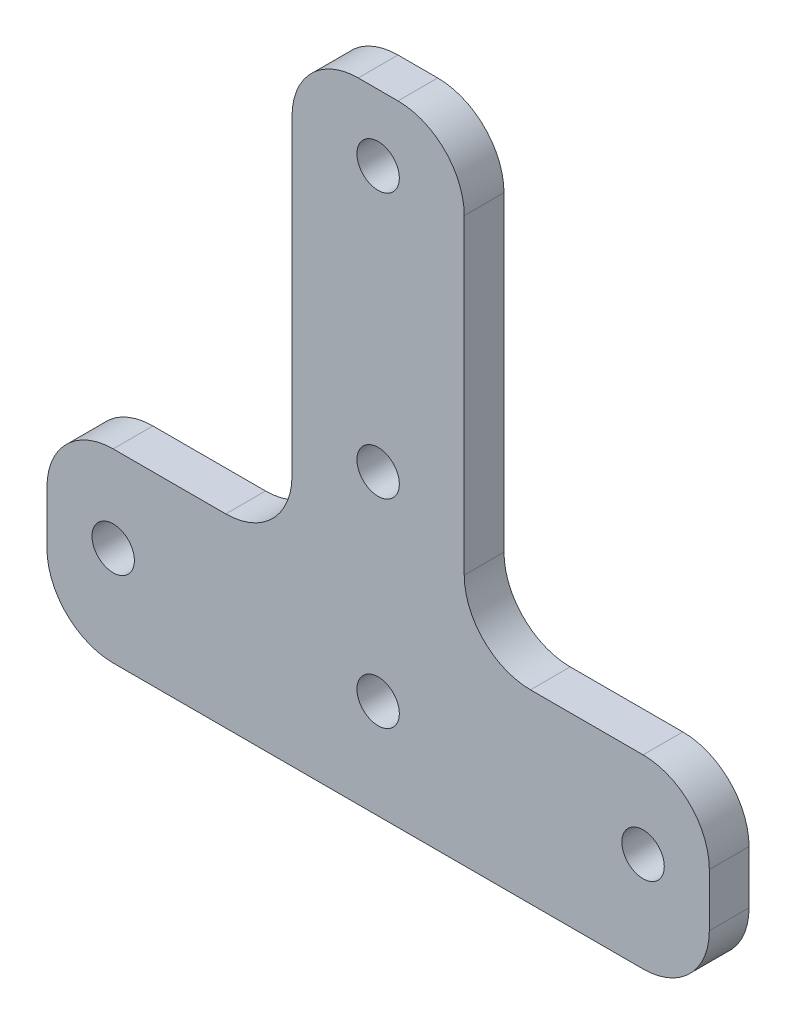
SolidWorks part; units mm, degrees
ref_plane "前视基准面" through (0, 0, 0) normal (0, 0, 1) x (1, 0, 0)
ref_plane "上视基准面" through (0, 0, 0) normal (0, 1, 0) x (1, 0, 0)
ref_plane "右视基准面" through (0, 0, 0) normal (1, 0, 0) x (0, 0, -1)
sketch "草图1" plane through (0, 0, 0) normal (0, 0, 1) x (1, 0, 0)
  line L0 (20, 0) -> (-20, 0) construction
  line L1 (0, 0) -> (0, 35) construction
  line L2 (-6.5, 6.5) -> (-25, 6.5)
  line L3 (-25, 6.5) -> (-25, -7.5)
  line L4 (-25, -7.5) -> (25, -7.5)
  line L5 (25, -7.5) -> (25, 6.5)
  line L6 (25, 6.5) -> (6.5, 6.5)
  line L7 (6.5, 6.5) -> (6.5, 40)
  line L8 (6.5, 40) -> (-6.5, 40)
  line L9 (-6.5, 40) -> (-6.5, 6.5)
  circle A0 centre (0, 35) radius 1.6
  circle A1 centre (0, 15) radius 1.6
  circle A2 centre (0, 0) radius 1.6
  circle A3 centre (20, 0) radius 1.6
  circle A4 centre (-20, 0) radius 1.6
  point P4 (0, 0)
  dimension "D1" = 3.2
  dimension "D2" = 15
  dimension "D3" = 20
  dimension "D7" = 5
  dimension "D9" = 5
  dimension "D4" = 40
  dimension "D5" = 6.5
  dimension "D6" = 6.5
  dimension "D8" = 6.5
  dimension "D10" = 7.5
  dimension "D11" = 6.5
  dimension "D12" = 5
extrude "凸台-拉伸1" add sketch "草图1" along normal blind 3
fillet "圆角1" radius 5 8 edges at (-6.5, 40, 1.5) (6.5, 40, 1.5) (25, 6.5, 1.5) (25, -7.5, 1.5) (-25, -7.5, 1.5) (-25, 6.5, 1.5) (-6.5, 6.5, 1.5) (6.5, 6.5, 1.5)
